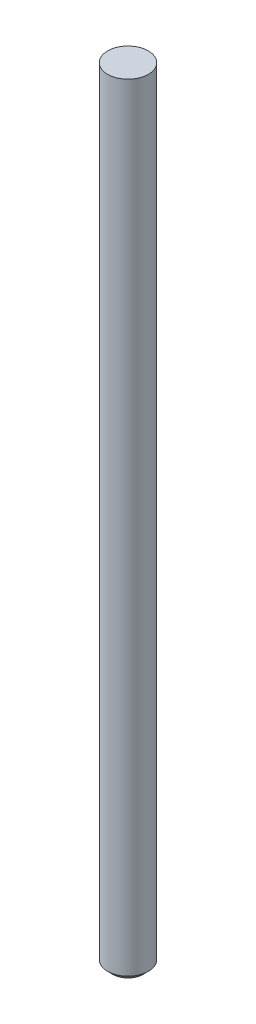
SolidWorks part; units mm, degrees
ref_plane "Front Plane" through (0, 0, 0) normal (0, 0, 1) x (1, 0, 0)
ref_plane "Top Plane" through (0, 0, 0) normal (0, 1, 0) x (1, 0, 0)
ref_plane "Right Plane" through (0, 0, 0) normal (1, 0, 0) x (0, 0, -1)
sketch "Sketch1" plane through (0, 0, 0) normal (0, 1, 0) x (1, 0, 0)
  circle A0 centre (0, 0) radius 3.9
  dimension "D1" = 7.8
extrude "Boss-Extrude1" add sketch "Sketch1" along normal blind 150
chamfer "Chamfer1" distance 1 angle 45 1 edges at (0, 0, 3.9)
cosmetic thread "Cosmetic Thread1" parameters "D1"=130, "D2"=4.891
